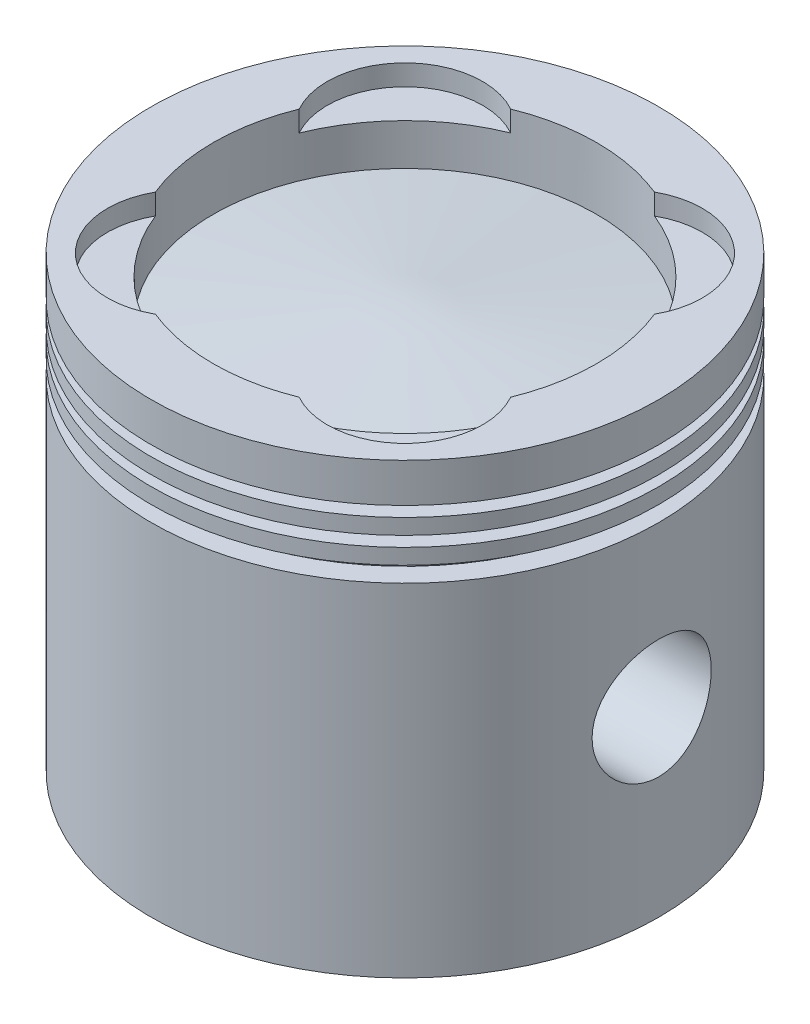
SolidWorks part; units mm, degrees
ref_plane "Front Plane" through (0, 0, 0) normal (0, 0, 1) x (1, 0, 0)
ref_plane "Top Plane" through (0, 0, 0) normal (0, 1, 0) x (1, 0, 0)
ref_plane "Right Plane" through (0, 0, 0) normal (1, 0, 0) x (0, 0, -1)
sketch "Sketch1" plane through (0, 0, 0) normal (0, 0, 1) x (1, 0, 0)
  line L0 (-1000, 0) -> (49000, 0) construction
  line L2 (0, -1000) -> (0, 35.5542) construction
  line L4 (0, -43) -> (0, 43) construction
  line L5 (37, 43.5542) -> (48.9969, 43.5542)
  line L6 (48.9969, 43.5542) -> (48.9969, 36)
  line L7 (49, -43) -> (42, -43)
  line L8 (48.9969, 36) -> (45, 36)
  line L9 (45, 36) -> (45, 34)
  line L10 (45, 34) -> (49, 34)
  line L11 (49, 34) -> (49, 31)
  line L12 (49, 31) -> (45, 31)
  line L13 (45, 31) -> (45, 29)
  line L14 (45, 29) -> (49, 29)
  line L15 (49, 29) -> (49, 26)
  line L16 (49, 26) -> (45, 26)
  line L17 (45, 26) -> (45, 23)
  line L18 (45, 23) -> (49, 23)
  line L19 (49, 23) -> (49, -43)
  line L20 (0, 20) -> (39, 20)
  line L21 (42, -43) -> (42, -40)
  line L22 (39, 20) -> (39, 12.3502)
  line L23 (39, 12.3502) -> (20, 9)
  line L24 (20, 9) -> (20, -25)
  line L25 (20, -25) -> (45, -29.4082)
  line L26 (45, -29.4082) -> (45, -40)
  line L27 (42, -40) -> (45, -40)
  line L28 (20, -8) -> (55.3375, -8) construction
  line L29 (37, 43.5542) -> (37, 31.5542)
  line L30 (37, 31.5542) -> (0, 35.5542)
  line L31 (0, 43) -> (0, 49000) construction
  line L32 (0, 35.5542) -> (0, 20)
  point P8 (0, 0)
  dimension "D1" = 86
  dimension "D2" = 49
  dimension "D3" = 66
  dimension "D4" = 69
  dimension "D5" = 72
  dimension "D6" = 74
  dimension "D7" = 77
  dimension "D8" = 79
  dimension "D9" = 45
  dimension "D10" = 45
  dimension "D11" = 45
  dimension "D12" = 49
  dimension "D13" = 49
  dimension "D14" = 49
  dimension "D15" = 3
  dimension "D16" = 20
  dimension "D17" = 34
  dimension "D18" = 63
  dimension "D19" = 39
  dimension "D20" = 100
  dimension "D21" = 100
  dimension "D22" = 42
  dimension "D23" = 45
  dimension "D24" = 35
  dimension "D25" = 37
  dimension "D26" = 12
  dimension "D27" = 8
  dimension "D28" = 43
  dimension "D29" = 35.5542
revolve "Revolve1" add sketch "Sketch1" angle 360 about L31
sketch "Sketch10" plane through (0, 0, 0) normal (1, 0, 0) x (0, 0, -1)
  line L0 (0, -201000) -> (0, 35.5542) construction
  line L1 (-49, -43) -> (49, -43) construction
  circle A0 centre (0, -8) radius 11.5
  dimension "D1" = 23
  dimension "D2" = 35
extrude "Cut-Extrude1" cut sketch "Sketch10" against normal mid plane 140
sketch "Sketch12" plane through (0, 43.5542, 0) normal (0, 1, 0) x (1, 0, 0)
  line L0 (0, 0) -> (-21.2132, 21.2132) construction
  line L2 (-201000, 0) -> (249000, 0) construction
  circle A6 centre (0, 0) radius 30 construction
  circle A7 centre (-21.2132, 21.2132) radius 15
  dimension "D1" = 60
  dimension "D2" = 45
  dimension "D3" = 30
extrude "Cut-Extrude2" cut sketch "Sketch12" against normal blind 4
pattern_circular "CirPattern1" count 4 over 360 about axis through (0, 0, 0) along (0, 1, 0) of "Cut-Extrude2"
